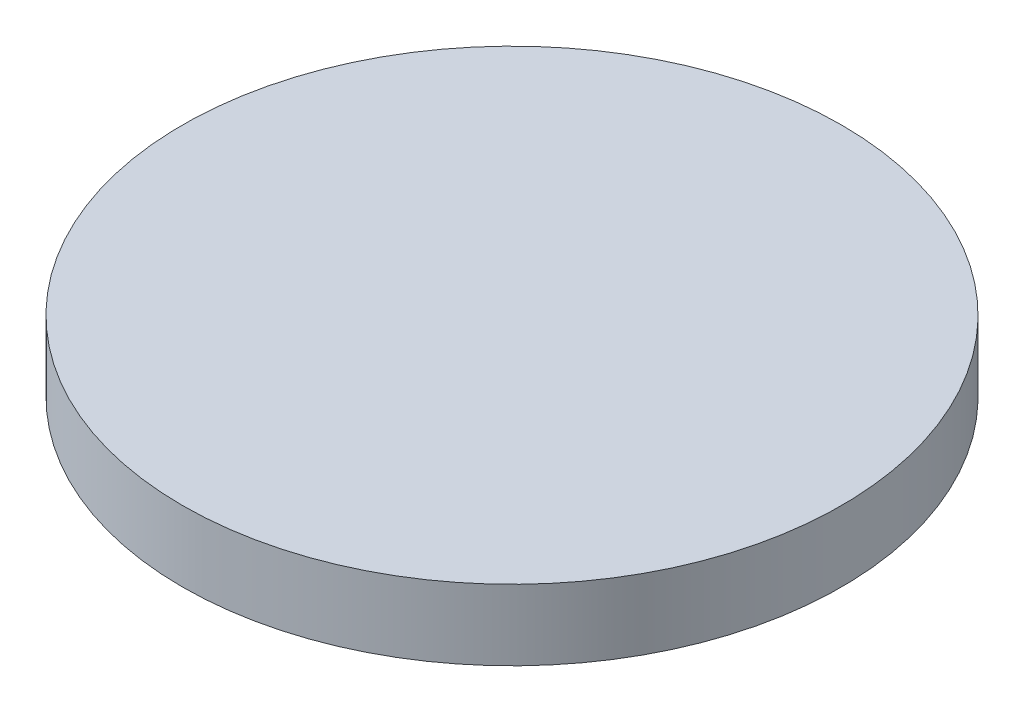
SolidWorks part; units mm, degrees
ref_plane "Front Plane" through (0, 0, 0) normal (0, 0, 1) x (1, 0, 0)
ref_plane "Top Plane" through (0, 0, 0) normal (0, 1, 0) x (1, 0, 0)
ref_plane "Right Plane" through (0, 0, 0) normal (1, 0, 0) x (0, 0, -1)
sketch "Sketch1" plane through (0, 0, 0) normal (0, 1, 0) x (1, 0, 0)
  circle A0 centre (0, 0) radius 88.9
  dimension "D1" = 177.8
extrude "Boss-Extrude1" add sketch "Sketch1" along normal blind 19.05
